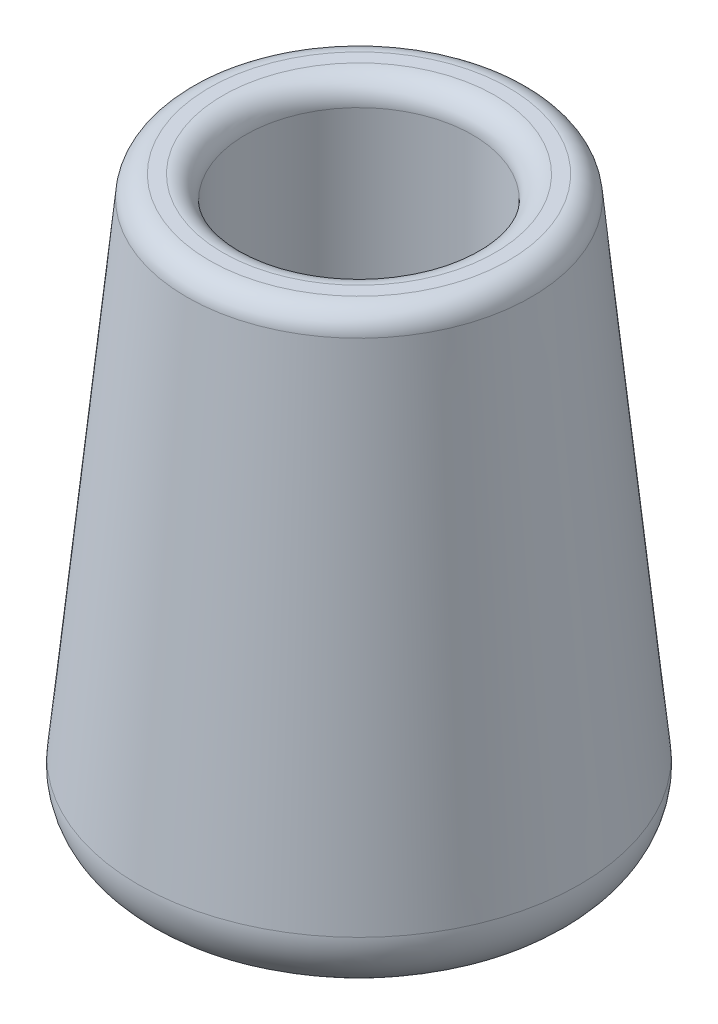
SolidWorks part; units mm, degrees
material "Silicon Rubber"
ref_plane "Front Plane" through (0, 0, 0) normal (0, 0, 1) x (1, 0, 0)
ref_plane "Top Plane" through (0, 0, 0) normal (0, 1, 0) x (1, 0, 0)
ref_plane "Right Plane" through (0, 0, 0) normal (1, 0, 0) x (0, 0, -1)
ref_plane "Plane1" through (0, 50, 0) normal (0, 1, 0) x (1, 0, 0)
sketch "Sketch1" plane through (0, 0, 0) normal (0, 1, 0) x (1, 0, 0)
  circle A0 centre (0, 0) radius 20
  dimension "D1" = 40
sketch "Sketch2" plane through (0, 50, 0) normal (0, 1, 0) x (1, 0, 0)
  circle A0 centre (0, 0) radius 15
  dimension "D1" = 30
loft "Loft1" add profiles "Sketch2", "Sketch1"
sketch "Sketch3" plane through (0, 50, 0) normal (0, 1, 0) x (1, 0, 0)
  circle A0 centre (0, 0) radius 10
  dimension "D1" = 20
extrude "Cut-Extrude1" cut sketch "Sketch3" against normal blind 20 and the other way through all
fillet "Fillet1" radius 5 1 edges at (0, 0, 20)
fillet "Fillet2" radius 2 2 edges at (0, 50, 15) (0, 50, 10)
